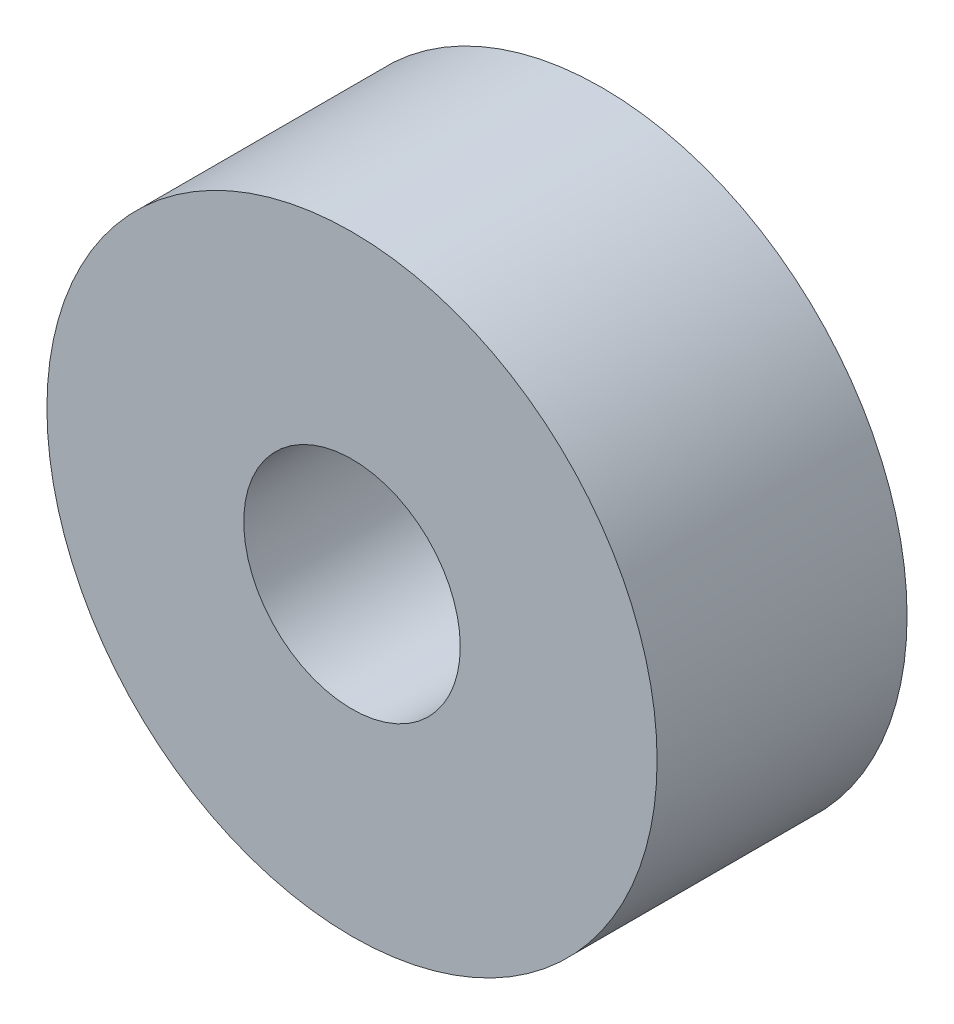
SolidWorks part; units mm, degrees
ref_plane "Front Plane" through (0, 0, 0) normal (0, 0, 1) x (1, 0, 0)
ref_plane "Top Plane" through (0, 0, 0) normal (0, 1, 0) x (1, 0, 0)
ref_plane "Right Plane" through (0, 0, 0) normal (1, 0, 0) x (0, 0, -1)
sketch "Sketch1" plane through (0, 0, 0) normal (0, 0, 1) x (1, 0, 0)
  circle A0 centre (0, 0) radius 2.75
  circle A1 centre (0, 0) radius 7.75
  dimension "D1" = 5.5
  dimension "D3" = 15.5
  dimension "D2" = 5
extrude "Boss-Extrude1" add sketch "Sketch1" along normal mid plane 6.35
